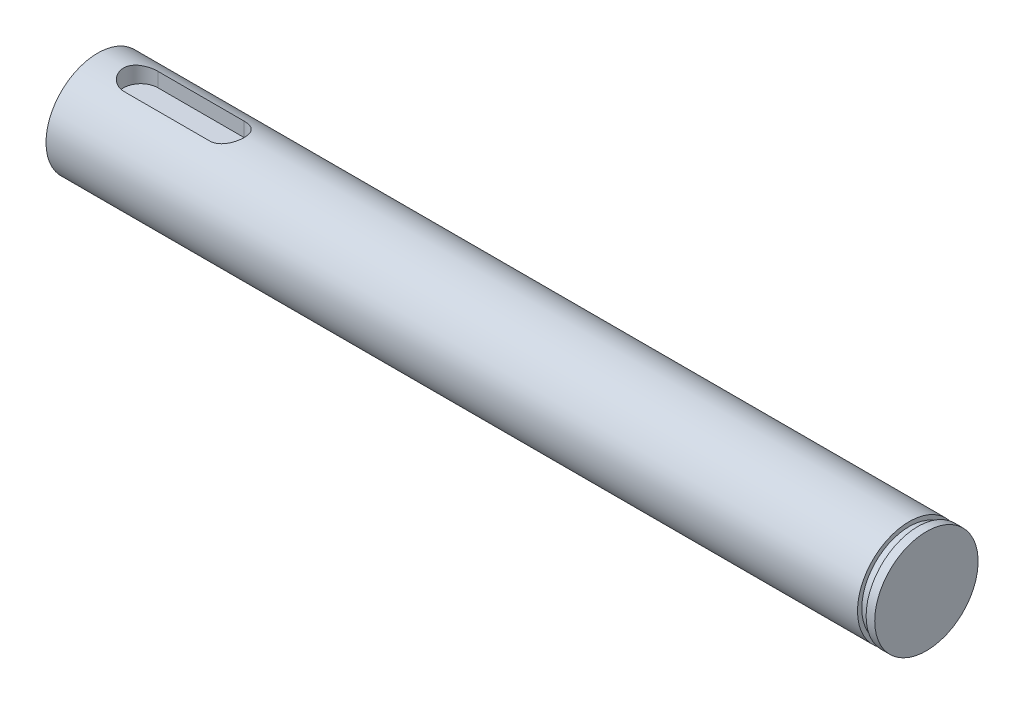
SolidWorks part; units mm, degrees
ref_plane "正面" through (0, 0, 0) normal (0, 0, 1) x (1, 0, 0)
ref_plane "平面" through (0, 0, 0) normal (0, 1, 0) x (1, 0, 0)
ref_plane "右側面" through (0, 0, 0) normal (1, 0, 0) x (0, 0, -1)
sketch "ｽｹｯﾁ2" plane through (0, 0, 0) normal (0, 0, 1) x (1, 0, 0)
  line L1 (0, 0) -> (96.2, 0)
  line L2 (0, 0) -> (0, 6)
  line L3 (0, 6) -> (96.2, 6)
  line L4 (96.2, 0) -> (96.2, 6)
  line L5 (48.1, 6) -> (48.1, 0) construction
  line L6 (0, 3) -> (96.2, 3) construction
  line L7 (1, 6) -> (2, 6)
  line L13 (94.2, 6) -> (95.2, 6)
  line L14 (94.2, 6) -> (94.2, 5.5)
  line L15 (94.2, 5.5) -> (95.2, 5.5)
  line L16 (95.2, 6) -> (95.2, 5.5)
  line L17 (94.7, 5.5) -> (94.7, 6) construction
  line L18 (94.2, 5.75) -> (95.2, 5.75) construction
  point P50 (1.5, 5.75)
  point P64 (48.1, 3)
  point P99 (94.7, 5.75)
  dimension "D1" = 6
  dimension "D2" = 96.2
  dimension "D6" = 1
  dimension "D7" = 1
  dimension "D8" = 0.5
revolve "回転1" add sketch "ｽｹｯﾁ2" angle 360 about L1
ref_plane "平面1" through (0, 6, 0) normal (0, 1, 0) x (1, 0, 0)
sketch "ｽｹｯﾁ4" plane through (0, 6, 0) normal (0, 1, 0) x (1, 0, 0)
  line L0 (5, 0) -> (15, 0) construction
  line L1 (5, 2) -> (15, 2)
  line L2 (5, -2) -> (15, -2)
  line L3 (0, 6) -> (0, -6) construction
  arc A0 (5, 2) -> (5, -2) centre (5, 0) ccw
  arc A1 (15, -2) -> (15, 2) centre (15, 0) ccw
  point P3 (10, 0)
  dimension "D3" = 2
  dimension "D1" = 5
  dimension "D2" = 10
extrude "ｶｯﾄ - 押し出し1" cut sketch "ｽｹｯﾁ4" against normal blind 2
